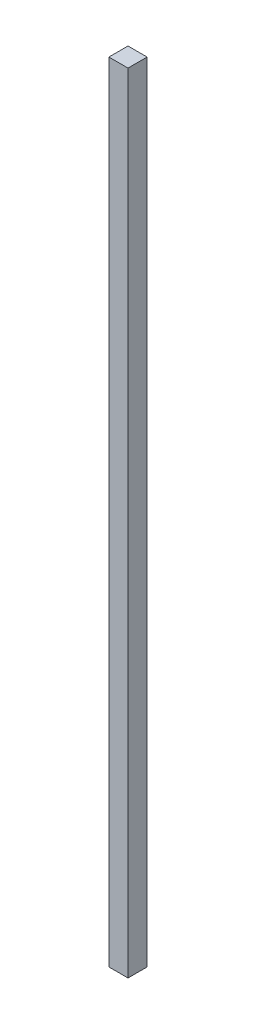
SolidWorks part; units mm, degrees
ref_plane "Front Plane" through (0, 0, 0) normal (0, 0, 1) x (1, 0, 0)
ref_plane "Top Plane" through (0, 0, 0) normal (0, 1, 0) x (1, 0, 0)
ref_plane "Right Plane" through (0, 0, 0) normal (1, 0, 0) x (0, 0, -1)
other "Configuration Table"
sketch "Sketch1" plane through (0, 0, 0) normal (0, 0, 1) x (1, 0, 0)
  line L1 (612.5, 250) -> (652.5, 250)
  line L2 (612.5, 250) -> (612.5, 1900)
  line L3 (612.5, 1900) -> (652.5, 1900)
  line L4 (652.5, 250) -> (652.5, 1900)
extrude "TOPPING_sag_kanal_kablo_kanali_1" add sketch "Sketch1" against normal blind 40 from offset 660 separate body
